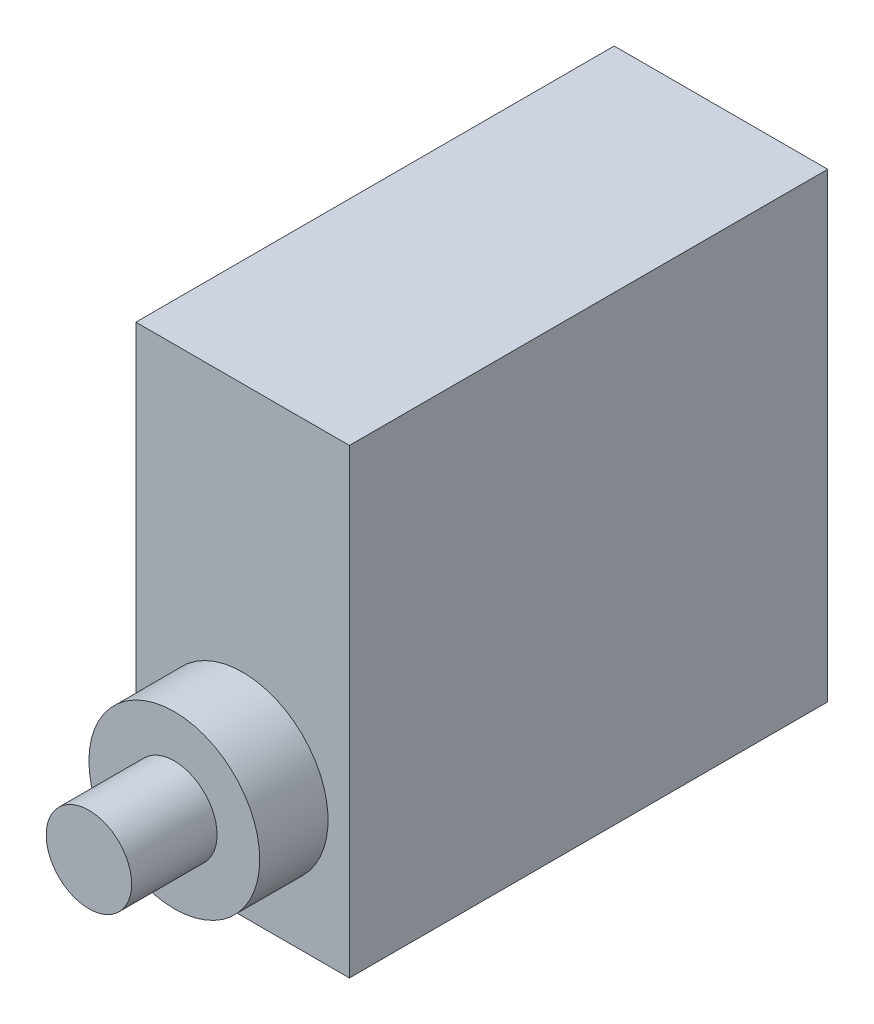
SolidWorks part; units mm, degrees
ref_plane "Front Plane" through (0, 0, 0) normal (0, 0, 1) x (1, 0, 0)
ref_plane "Top Plane" through (0, 0, 0) normal (0, 1, 0) x (1, 0, 0)
ref_plane "Right Plane" through (0, 0, 0) normal (1, 0, 0) x (0, 0, -1)
sketch "Sketch2" plane through (0, 0, 0) normal (0, 0, 1) x (1, 0, 0)
  line L1 (0, 0) -> (12.5, 0)
  line L2 (0, 0) -> (0, 27)
  line L3 (0, 27) -> (12.5, 27)
  line L4 (12.5, 0) -> (12.5, 27)
  dimension "D1" = 12.5
  dimension "D2" = 27
extrude "Boss-Extrude1" add sketch "Sketch2" along normal blind 28
sketch "Sketch3" plane through (0, 0, 28) normal (0, 0, 1) x (1, 0, 0)
  line L0 (6.25, 0) -> (6.25, 27) construction
  line L1 (0, 0) -> (12.5, 0) construction
  line L2 (12.5, 27) -> (0, 27) construction
  circle A0 centre (6.25, 7.3813) radius 5
  dimension "D1" = 10
extrude "Boss-Extrude2" add sketch "Sketch3" along normal blind 4
sketch "Sketch4" plane through (0, 0, 32) normal (0, 0, 1) x (1, 0, 0)
  circle A0 centre (6.25, 7.3813) radius 2.5
  dimension "D1" = 5
extrude "Boss-Extrude3" add sketch "Sketch4" along normal blind 5
